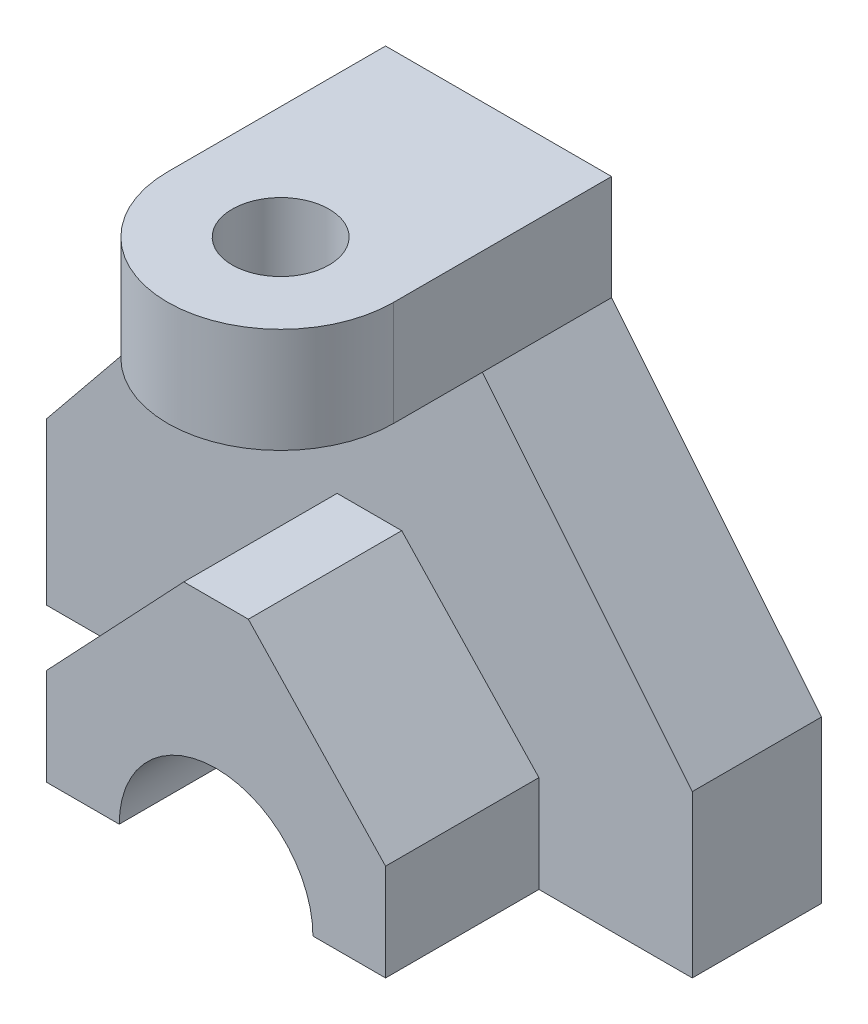
SolidWorks part; units mm, degrees
ref_plane "前视基准面" through (0, 0, 0) normal (0, 0, 1) x (1, 0, 0)
ref_plane "上视基准面" through (0, 0, 0) normal (0, 1, 0) x (1, 0, 0)
ref_plane "右视基准面" through (0, 0, 0) normal (1, 0, 0) x (0, 0, -1)
other "Configuration Table"
sketch "草图1" plane through (0, 0, 0) normal (0, 0, 1) x (1, 0, 0)
  line L0 (0, 0) -> (-40, 0)
  line L1 (0, 0) -> (0, 52)
  line L2 (-40, 0) -> (-40, 20)
  line L3 (0, 52) -> (-14, 52)
  line L4 (-14, 52) -> (-40, 20)
  dimension "D1" = 40
  dimension "D2" = 20
  dimension "D3" = 52
  dimension "D4" = 14
extrude "凸台-拉伸1" add sketch "草图1" along normal blind 16
mirror "镜向1" about plane through (0, 0, 16) normal (-1, 0, 0) of "凸台-拉伸1"
sketch "草图3" plane through (0, 52, 0) normal (0, 1, 0) x (1, 0, 0)
  line L0 (-14, 0) -> (-14, -27)
  line L1 (-14, 0) -> (14, 0)
  line L2 (14, 0) -> (14, -27)
  arc A0 (-14, -27) -> (14, -27) centre (0, -27) ccw
  dimension "D1" = 27
extrude "凸台-拉伸2" add sketch "草图3" along normal blind 13
sketch "草图4" plane through (0, 65, 0) normal (0, 1, 0) x (1, 0, 0)
  circle A0 centre (0, -27) radius 6
  dimension "D1" = 12
extrude "切除-拉伸1" cut sketch "草图4" against normal blind 13
sketch "草图5" plane through (0, 0, 16) normal (0, 0, 1) x (1, 0, 0)
  line L0 (0, 0) -> (-21, 0)
  line L1 (-40, 0) -> (40, 0) construction
  line L2 (-21, 0) -> (-21, 12)
  line L3 (-21, 12) -> (-4, 30)
  line L4 (0, 0) -> (0, 30)
  line L5 (0, 30) -> (-4, 30)
  dimension "D1" = 21
  dimension "D2" = 12
  dimension "D3" = 30
  dimension "D4" = 4
extrude "凸台-拉伸3" add sketch "草图5" along normal blind 19
mirror "镜向2" about plane through (0, 0, 35) normal (-1, 0, 0) of "凸台-拉伸3"
sketch "草图6" plane through (0, 0, 35) normal (0, 0, 1) x (1, 0, 0)
  line L0 (-12, 0) -> (12, 0)
  arc A0 (12, 0) -> (-12, 0) centre (0, 0) ccw
  dimension "D1" = 12
extrude "切除-拉伸2" cut sketch "草图6" against normal blind 35
